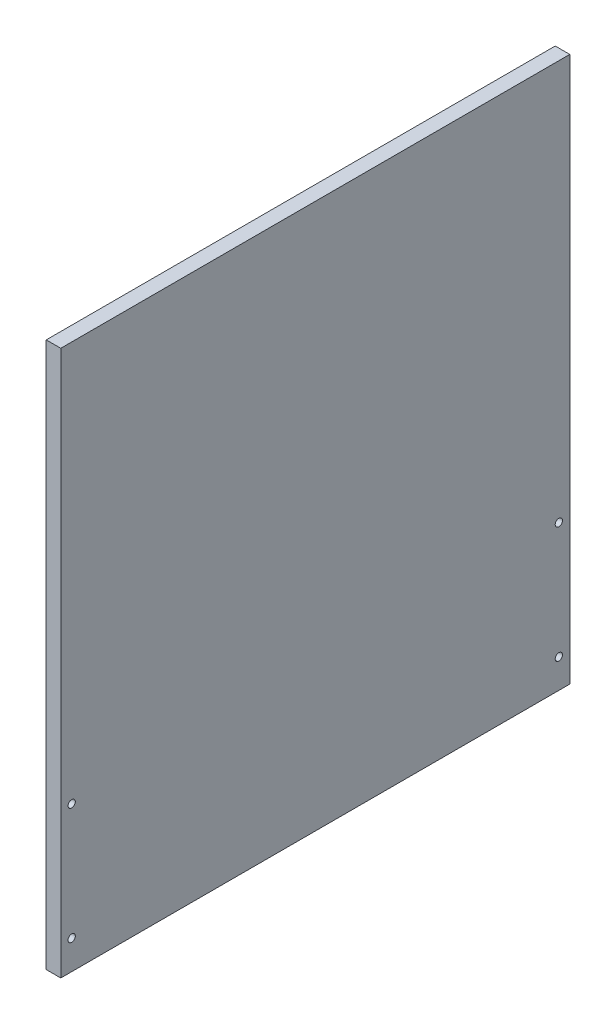
SolidWorks part; units mm, degrees
ref_plane "Front Plane" through (0, 0, 0) normal (0, 0, 1) x (1, 0, 0)
ref_plane "Top Plane" through (0, 0, 0) normal (0, 1, 0) x (1, 0, 0)
ref_plane "Right Plane" through (0, 0, 0) normal (1, 0, 0) x (0, 0, -1)
sketch "Sketch1" plane through (0, 0, 0) normal (1, 0, 0) x (0, 0, -1)
  line L1 (-140, -150) -> (140, -150)
  line L2 (-140, -150) -> (-140, 150)
  line L3 (-140, 150) -> (140, 150)
  line L4 (140, -150) -> (140, 150)
  line L5 (-140, -150) -> (140, 150) construction
  line L6 (-140, 150) -> (140, -150) construction
  point P0 (0, 0)
  dimension "D1" = 280
  dimension "D2" = 300
extrude "Boss-Extrude1" add sketch "Sketch1" along normal blind 8
sketch "Sketch2" plane through (0, 0, 0) normal (1, 0, 0) x (0, 0, -1)
  line L0 (0, -1000) -> (0, 49000) construction
  line L1 (-140, -150) -> (140, -150) construction
  circle A0 centre (134, -134) radius 2
  circle A1 centre (134, -70) radius 2
  dimension "D1" = 4
  dimension "D4" = 64
  dimension "D2" = 134
  dimension "D3" = 16
extrude "Cut-Extrude1" cut sketch "Sketch2" along normal through all
mirror "Mirror1" about plane through (0, 0, 0) normal (0, 0, 1) of "Cut-Extrude1"
